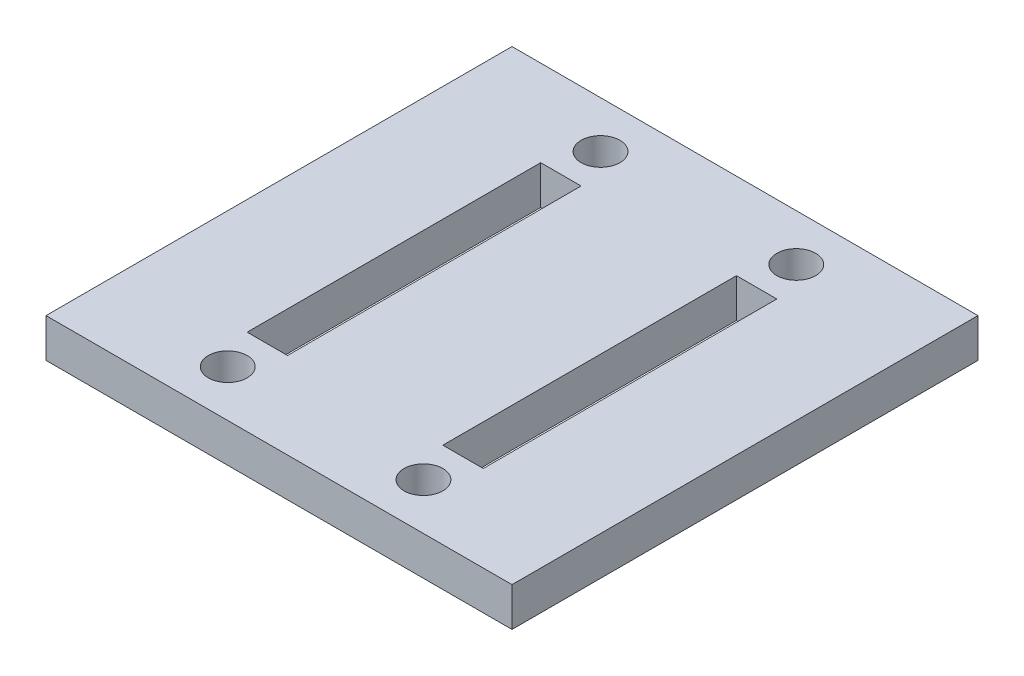
SolidWorks part; units mm, degrees
material "Plain Carbon Steel"
ref_plane "Front Plane" through (0, 0, 0) normal (0, 0, 1) x (1, 0, 0)
ref_plane "Top Plane" through (0, 0, 0) normal (0, 1, 0) x (1, 0, 0)
ref_plane "Right Plane" through (0, 0, 0) normal (1, 0, 0) x (0, 0, -1)
sketch "Sketch1" plane through (0, 0, 0) normal (0, 1, 0) x (1, 0, 0)
  line L1 (-38.1, -38.1) -> (38.1, -38.1)
  line L2 (-38.1, -38.1) -> (-38.1, 38.1)
  line L3 (-38.1, 38.1) -> (38.1, 38.1)
  line L4 (38.1, -38.1) -> (38.1, 38.1)
  line L5 (-38.1, -38.1) -> (38.1, 38.1) construction
  line L6 (-38.1, 38.1) -> (38.1, -38.1) construction
  point P0 (0, 0)
  point P6 (0, 38.1)
  dimension "D1" = 76.2
  dimension "D2" = 76.2
extrude "Boss-Extrude1" add sketch "Sketch1" along normal blind 6.35
sketch "Sketch2" plane through (0, 0, 0) normal (0, 1, 0) x (1, 0, 0)
  line L0 (0, 0) -> (0, 15.412) construction
  line L1 (12.7, -24.003) -> (19.304, -24.003)
  line L2 (12.7, -24.003) -> (12.7, 24.003)
  line L3 (12.7, 24.003) -> (19.304, 24.003)
  line L4 (19.304, -24.003) -> (19.304, 24.003)
  line L5 (12.7, -24.003) -> (19.304, 24.003) construction
  line L6 (12.7, 24.003) -> (19.304, -24.003) construction
  line L7 (-12.7, 24.003) -> (-19.304, -24.003) construction
  line L8 (-12.7, -24.003) -> (-19.304, 24.003) construction
  line L9 (-19.304, -24.003) -> (-19.304, 24.003)
  line L10 (-12.7, 24.003) -> (-19.304, 24.003)
  line L11 (-12.7, -24.003) -> (-12.7, 24.003)
  line L12 (-12.7, -24.003) -> (-19.304, -24.003)
  line L16 (0, 0) -> (6.0655, 0) construction
  line L18 (38.1, 38.1) -> (-38.1, 38.1) construction
  point P0 (16.002, 0)
  point P13 (-16.002, 0)
  dimension "D1" = 48.006
  dimension "D2" = 6.604
  dimension "D3" = 12.7
  dimension "D4" = 38.1
extrude "Cut-Extrude1" cut sketch "Sketch2" along normal through all
sketch "Sketch3" plane through (0, 0, 0) normal (0, 1, 0) x (1, 0, 0)
  line L0 (0, 0) -> (0, 9.3414) construction
  line L1 (0, 9.3414) -> (0, 0) construction
  line L2 (0, 0) -> (-6.602, 0) construction
  line L3 (38.1, 38.1) -> (-38.1, 38.1) construction
  line L4 (-38.1, 38.1) -> (-38.1, -38.1) construction
  circle A0 centre (-16.002, 30.48) radius 3.175
  circle A1 centre (-16.002, -30.48) radius 3.175
  circle A2 centre (16.002, -30.48) radius 3.175
  circle A3 centre (16.002, 30.48) radius 3.175
  dimension "D1" = 6.35
  dimension "D2" = 7.62
  dimension "D3" = 22.098
extrude "Cut-Extrude3" cut sketch "Sketch3" along normal through all
